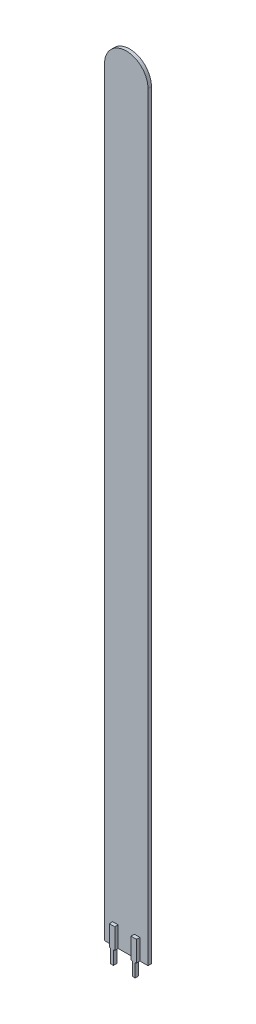
SolidWorks part; units mm, degrees
ref_plane "Plano frontal" through (0, 0, 0) normal (0, 0, 1) x (1, 0, 0)
ref_plane "Plano superior" through (0, 0, 0) normal (0, 1, 0) x (1, 0, 0)
ref_plane "Plano direito" through (0, 0, 0) normal (1, 0, 0) x (0, 0, -1)
sketch "Esboço3" plane through (0, 0, 0) normal (0, 0, 1) x (1, 0, 0)
  line L0 (0, 57.15) -> (0, 0) construction
  line L1 (3.175, -57.15) -> (-3.175, -57.15)
  line L2 (3.175, -57.15) -> (3.175, 53.975)
  line L4 (-3.175, -57.15) -> (-3.175, 53.975)
  line L5 (3.175, -57.15) -> (0, 0) construction
  line L6 (0, 0) -> (-3.175, -57.15) construction
  line L7 (-3.175, 53.975) -> (3.175, 53.975) construction
  arc A0 (3.175, 53.975) -> (-3.175, 53.975) centre (0, 53.975) ccw
  point P0 (0, 0)
  dimension "D3" = 6.35
  dimension "D1" = 6.35
  dimension "D2" = 114.3
  dimension "D4" = 57.15
extrude "Ressalto-extrusão1" add sketch "Esboço3" along normal mid plane 0.5
sketch "Esboço4" plane through (0, 0, 0.25) normal (0, 0, 1) x (1, 0, 0)
  line L0 (0, 0) -> (0, -57.15) construction
  line L1 (-3.175, -57.15) -> (3.175, -57.15) construction
  line L2 (-1.5875, -54.15) -> (-1.5875, -59.15) construction
  line L3 (-1.9875, -54.15) -> (-1.1875, -54.15)
  line L4 (-1.9875, -54.15) -> (-1.9875, -57.15)
  line L5 (-1.9875, -57.15) -> (-1.9375, -57.15)
  line L6 (-1.1875, -54.15) -> (-1.1875, -57.15)
  line L7 (-3.175, 53.975) -> (-3.175, -57.15) construction
  line L8 (-1.7875, -57.3) -> (-1.7875, -59.15)
  line L9 (-1.3875, -59.15) -> (-1.7875, -59.15)
  line L10 (-1.3875, -57.3) -> (-1.3875, -59.15)
  line L11 (-1.2375, -57.15) -> (-1.1875, -57.15)
  line L12 (-1.9375, -57.15) -> (-1.9875, -57.15)
  line L13 (-1.7875, -57.3) -> (-1.7875, -59.15)
  line L14 (-1.3875, -57.3) -> (-1.3875, -59.15)
  line L15 (-1.9875, -54.15) -> (-1.9875, -57.15)
  line L16 (-1.1875, -57.15) -> (-1.2375, -57.15)
  line L17 (-1.1875, -54.15) -> (-1.1875, -57.15)
  line L18 (-1.9875, -54.15) -> (-1.9875, -57.15)
  line L20 (-1.9875, -57.15) -> (-1.9375, -57.15)
  line L22 (-1.1875, -54.15) -> (-1.1875, -57.15)
  line L23 (-1.7875, -57.3) -> (-1.7875, -59.15)
  line L24 (-1.3875, -57.3) -> (-1.3875, -59.15)
  line L25 (-1.2375, -57.15) -> (-1.1875, -57.15)
  line L26 (-1.9375, -57.15) -> (-1.9875, -57.15)
  line L27 (-1.7875, -57.3) -> (-1.7875, -59.15)
  line L28 (-1.3875, -57.3) -> (-1.3875, -59.15)
  line L30 (-1.9875, -54.15) -> (-1.9875, -57.15)
  line L32 (-1.1875, -57.15) -> (-1.2375, -57.15)
  line L33 (-1.1875, -54.15) -> (-1.1875, -57.15)
  arc A0 (-1.2375, -57.15) -> (-1.3875, -57.3) centre (-1.2375, -57.3) ccw
  arc A1 (-1.7875, -57.3) -> (-1.9375, -57.15) centre (-1.9375, -57.3) ccw
  arc A2 (-1.3875, -57.3) -> (-1.2375, -57.15) centre (-1.2375, -57.3) cw
  arc A3 (-1.9375, -57.15) -> (-1.7875, -57.3) centre (-1.9375, -57.3) cw
  arc A8 (-1.2375, -57.15) -> (-1.3875, -57.3) centre (-1.2375, -57.3) ccw
  arc A9 (-1.7875, -57.3) -> (-1.9375, -57.15) centre (-1.9375, -57.3) ccw
  arc A10 (-1.3875, -57.3) -> (-1.2375, -57.15) centre (-1.2375, -57.3) cw
  arc A11 (-1.9375, -57.15) -> (-1.7875, -57.3) centre (-1.9375, -57.3) cw
  point P19 (-1.3875, -57.15)
  point P22 (-1.7875, -57.15)
  line M6 (-3.175, -57.15) -> (3.175, -57.15)
  dimension "D6" = 0.15
  dimension "D1" = 1.5875
  dimension "D2" = 0.8
  dimension "D3" = 3
  dimension "D4" = 5
  dimension "D5" = 0.2
extrude "Ressalto-extrusão2" add sketch "Esboço4" along normal blind 0.5 contours L6 L3 L4 M6 | A1 L8 L9 L10 A0 M6
mirror "Espelhar2" about plane through (0, 0, 0) normal (1, 0, 0) of "Ressalto-extrusão2"
